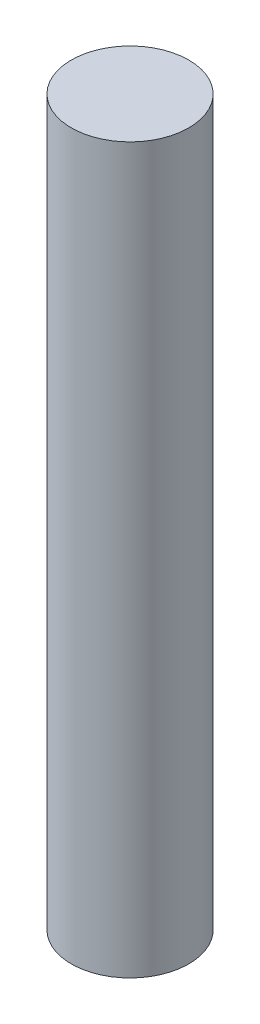
SolidWorks part; units mm, degrees
ref_plane "Alzado" through (0, 0, 0) normal (0, 0, 1) x (1, 0, 0)
ref_plane "Planta" through (0, 0, 0) normal (0, 1, 0) x (1, 0, 0)
ref_plane "Vista lateral" through (0, 0, 0) normal (1, 0, 0) x (0, 0, -1)
sketch "Croquis1" plane through (0, 0, 0) normal (0, 1, 0) x (1, 0, 0)
  circle A0 centre (0, 0) radius 4.7625
  dimension "D1" = 9.525
extrude "Saliente-Extruir1" add sketch "Croquis1" along normal blind 58.68
sketch "Croquis2" plane through (0, 58.68, 0) normal (0, 1, 0) x (1, 0, 0)
  circle A0 centre (0, 0) radius 2.5
  dimension "D1" = 5
